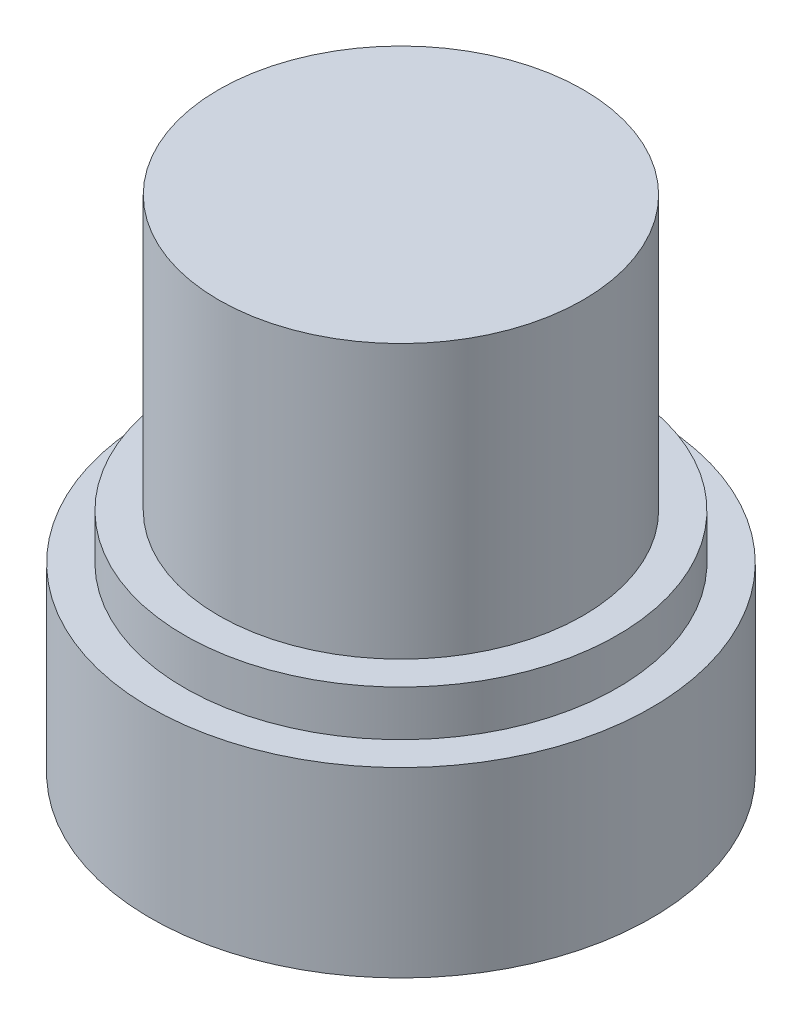
SolidWorks part; units mm, degrees
ref_plane "Front Plane" through (0, 0, 0) normal (0, 0, 1) x (1, 0, 0)
ref_plane "Top Plane" through (0, 0, 0) normal (0, 1, 0) x (1, 0, 0)
ref_plane "Right Plane" through (0, 0, 0) normal (1, 0, 0) x (0, 0, -1)
sketch "Sketch1" plane through (0, 0, 0) normal (0, 0, 1) x (1, 0, 0)
  line L0 (0, 0) -> (2.75, 0)
  line L1 (2.75, 0) -> (2.75, 2)
  line L2 (2.75, 2) -> (2.375, 2)
  line L3 (2.375, 2) -> (2.375, 2.5)
  line L4 (2.375, 2.5) -> (2, 2.5)
  line L5 (2, 2.5) -> (2, 5.5)
  line L6 (2, 5.5) -> (0, 5.5)
  line L7 (0, 5.5) -> (0, 0) construction
  line L8 (0, 0) -> (0, 5.5)
  dimension "D1" = 2.75
  dimension "D2" = 2
  dimension "D3" = 0.5
  dimension "D4" = 3
  dimension "D5" = 2
revolve "Revolve1" add sketch "Sketch1" angle 360 about L7
